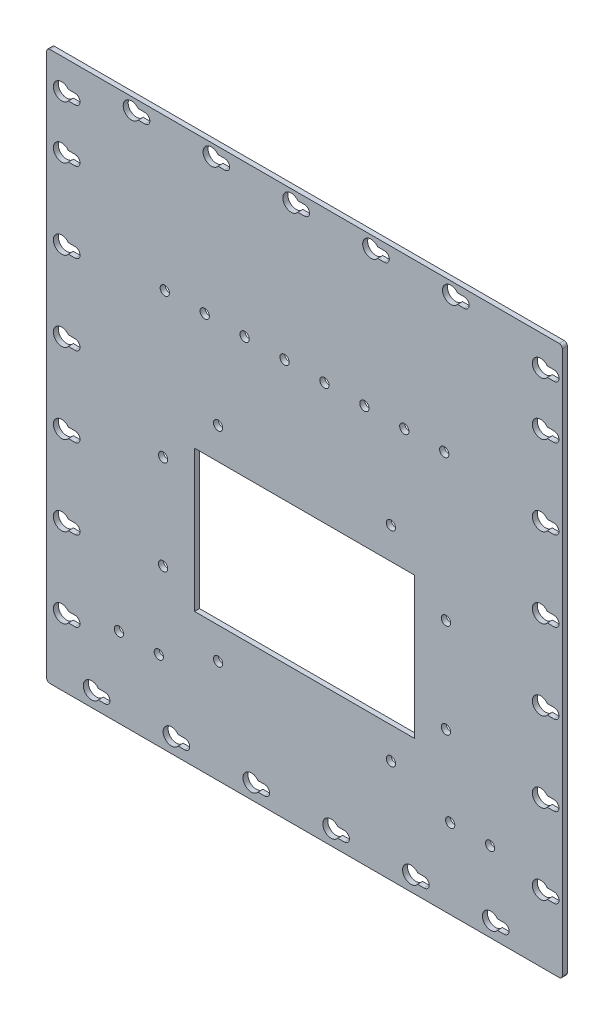
SolidWorks part; units mm, degrees
material "6061 Alloy"
ref_plane "Front Plane" through (0, 0, 0) normal (0, 0, 1) x (1, 0, 0)
ref_plane "Top Plane" through (0, 0, 0) normal (0, 1, 0) x (1, 0, 0)
ref_plane "Right Plane" through (0, 0, 0) normal (1, 0, 0) x (0, 0, -1)
sketch "Sketch1" plane through (0, 0, 0) normal (0, 0, 1) x (1, 0, 0)
  line L0 (0, 0) -> (0, -174.745)
  line L3 (0, -174.745) -> (165.1, -174.745)
  line L5 (0, 0) -> (165.1, 0)
  line L6 (165.1, -174.745) -> (165.1, 0)
  line L7 (82.55, 0) -> (82.55, -174.745) construction
  line L8 (31.75, -2.2625) -> (29.6344, -2.2625)
  line L9 (31.75, -5.4375) -> (29.6344, -5.4375)
  line L10 (9.525, -24.9325) -> (7.4094, -24.9325)
  line L11 (9.525, -28.1075) -> (7.4094, -28.1075)
  line L12 (161.925, -24.9325) -> (159.8094, -24.9325)
  line L13 (161.925, -28.1075) -> (159.8094, -28.1075)
  line L14 (57.15, -2.2625) -> (55.0344, -2.2625)
  line L15 (57.15, -5.4375) -> (55.0344, -5.4375)
  line L16 (82.55, -2.2625) -> (80.4344, -2.2625)
  line L17 (82.55, -5.4375) -> (80.4344, -5.4375)
  line L18 (107.95, -2.2625) -> (105.8344, -2.2625)
  line L19 (107.95, -5.4375) -> (105.8344, -5.4375)
  line L20 (133.35, -2.2625) -> (131.2344, -2.2625)
  line L21 (133.35, -5.4375) -> (131.2344, -5.4375)
  line L22 (9.525, -50.3325) -> (7.4094, -50.3325)
  line L23 (9.525, -53.5075) -> (7.4094, -53.5075)
  line L24 (161.925, -50.3325) -> (159.8094, -50.3325)
  line L25 (161.925, -53.5075) -> (159.8094, -53.5075)
  line L26 (9.525, -75.7325) -> (7.4094, -75.7325)
  line L27 (9.525, -78.9075) -> (7.4094, -78.9075)
  line L28 (161.925, -75.7325) -> (159.8094, -75.7325)
  line L29 (161.925, -78.9075) -> (159.8094, -78.9075)
  line L30 (9.525, -101.1325) -> (7.4094, -101.1325)
  line L31 (9.525, -104.3075) -> (7.4094, -104.3075)
  line L32 (161.925, -101.1325) -> (159.8094, -101.1325)
  line L33 (161.925, -104.3075) -> (159.8094, -104.3075)
  line L34 (9.525, -126.5325) -> (7.4094, -126.5325)
  line L35 (9.525, -129.7075) -> (7.4094, -129.7075)
  line L36 (161.925, -126.5325) -> (159.8094, -126.5325)
  line L37 (161.925, -129.7075) -> (159.8094, -129.7075)
  line L38 (9.525, -151.9325) -> (7.4094, -151.9325)
  line L39 (9.525, -155.1075) -> (7.4094, -155.1075)
  line L40 (161.925, -151.9325) -> (159.8094, -151.9325)
  line L41 (161.925, -155.1075) -> (159.8094, -155.1075)
  line L42 (19.05, -168.395) -> (16.9344, -168.395)
  line L43 (19.05, -171.57) -> (16.9344, -171.57)
  line L44 (44.45, -168.395) -> (42.3344, -168.395)
  line L45 (44.45, -171.57) -> (42.3344, -171.57)
  line L46 (69.85, -168.395) -> (67.7344, -168.395)
  line L47 (69.85, -171.57) -> (67.7344, -171.57)
  line L48 (95.25, -168.395) -> (93.1344, -168.395)
  line L49 (95.25, -171.57) -> (93.1344, -171.57)
  line L50 (120.65, -168.395) -> (118.5344, -168.395)
  line L51 (120.65, -171.57) -> (118.5344, -171.57)
  line L52 (146.05, -168.395) -> (143.9344, -168.395)
  line L53 (146.05, -171.57) -> (143.9344, -171.57)
  line L54 (0.5, 0) -> (0.5, -174.745)
  line L55 (164.6, -174.745) -> (164.6, 0)
  line L56 (0.5, -174.745) -> (164.6, -174.745)
  line L57 (9.525, -8.1) -> (7.4094, -8.1)
  line L58 (9.525, -11.275) -> (7.4094, -11.275)
  line L59 (161.925, -8.1) -> (159.8094, -8.1)
  line L60 (161.925, -11.275) -> (159.8094, -11.275)
  circle A41 centre (9.525, -153.52) radius 1.5875
  circle A42 centre (19.05, -169.9825) radius 1.5875
  circle A43 centre (9.525, -128.12) radius 1.5875
  circle A44 centre (9.525, -102.72) radius 1.5875
  circle A45 centre (9.525, -77.32) radius 1.5875
  circle A46 centre (9.525, -51.92) radius 1.5875
  circle A47 centre (9.525, -26.52) radius 1.5875
  circle A49 centre (44.45, -169.9825) radius 1.5875
  circle A50 centre (69.85, -169.9825) radius 1.5875
  circle A51 centre (95.25, -169.9825) radius 1.5875
  circle A52 centre (120.65, -169.9825) radius 1.5875
  circle A68 centre (146.05, -169.9825) radius 1.5875
  circle A69 centre (107.95, -3.85) radius 1.5875
  circle A70 centre (82.55, -3.85) radius 1.5875
  circle A71 centre (57.15, -3.85) radius 1.5875
  circle A72 centre (9.525, -1.12) radius 1.5875 [skipped]
  circle A73 centre (133.35, -3.85) radius 1.5875
  circle A74 centre (31.75, -3.85) radius 1.5875
  circle A75 centre (161.925, -26.52) radius 1.5875
  circle A76 centre (161.925, -51.92) radius 1.5875
  circle A77 centre (161.925, -77.32) radius 1.5875
  circle A78 centre (161.925, -102.72) radius 1.5875
  circle A79 centre (161.925, -128.12) radius 1.5875
  circle A80 centre (161.925, -153.52) radius 1.5875
  circle A81 centre (27.5125, -3.85) radius 2.65
  circle A83 centre (5.2875, -26.52) radius 2.65
  circle A84 centre (157.6875, -26.52) radius 2.65
  circle A85 centre (52.9125, -3.85) radius 2.65
  circle A86 centre (78.3125, -3.85) radius 2.65
  circle A87 centre (103.7125, -3.85) radius 2.65
  circle A88 centre (129.1125, -3.85) radius 2.65
  circle A89 centre (5.2875, -51.92) radius 2.65
  circle A90 centre (157.6875, -51.92) radius 2.65
  circle A91 centre (5.2875, -77.32) radius 2.65
  circle A92 centre (157.6875, -77.32) radius 2.65
  circle A93 centre (5.2875, -102.72) radius 2.65
  circle A94 centre (157.6875, -102.72) radius 2.65
  circle A95 centre (5.2875, -128.12) radius 2.65
  circle A96 centre (157.6875, -128.12) radius 2.65
  circle A97 centre (5.2875, -153.52) radius 2.65
  circle A98 centre (157.6875, -153.52) radius 2.65
  circle A99 centre (14.8125, -169.9825) radius 2.65
  circle A100 centre (40.2125, -169.9825) radius 2.65
  circle A101 centre (65.6125, -169.9825) radius 2.65
  circle A102 centre (91.0125, -169.9825) radius 2.65
  circle A103 centre (116.4125, -169.9825) radius 2.65
  circle A104 centre (141.8125, -169.9825) radius 2.65
  circle A107 centre (9.525, -9.6875) radius 1.5875
  circle A108 centre (5.2875, -9.6875) radius 2.65
  circle A109 centre (161.925, -9.6875) radius 1.5875
  circle A110 centre (157.6875, -9.6875) radius 2.65
  dimension "D3" = 3.175
  dimension "D8" = 3.175
  dimension "D21" = 5.3
  dimension "D33" = 5.3
  dimension "D1" = 165.1
  dimension "D2" = 174.745
  dimension "D5" = 9.525
  dimension "D4" = 21.225
  dimension "D6" = 19.05
  dimension "D7" = 4.7625
  dimension "D9" = 25.4
  dimension "D10" = 25.4
  dimension "D15" = 25.4
  dimension "D12" = 3.85
  dimension "D13" = 31.75
  dimension "D17" = 31.75
  dimension "D18" = 3.175
  dimension "D20" = 25.4
  dimension "D23" = 25.4
  dimension "D25" = 25.4
  dimension "D27" = 25.4
  dimension "D28" = 0.5
  dimension "D29" = 0.5
  dimension "D34" = 16.8325
  dimension "D35" = 5.8375
  dimension "D11" = 7
  dimension "D14" = 5
  dimension "D16" = 5
  dimension "D19" = 6
  dimension "D22" = 5
  dimension "D24" = 6
  dimension "D26" = 6
extrude "Boss-Extrude1" add sketch "Sketch1" along normal blind 1.5875
fillet "Fillet1" radius 1 4 edges at (164.6, 0, 0.7937) (164.6, -174.745, 0.7937) (0.5, -174.745, 0.7937) (0.5, 0, 0.7937)
sketch "Sketch2" plane through (0, 0, 1.5875) normal (0, 0, 1) x (1, 0, 0)
  line L0 (127.55, -94.3725) -> (37.55, -94.3725) construction
  line L1 (47.55, -86.8725) -> (117.55, -86.8725)
  line L3 (47.55, -131.8725) -> (117.55, -131.8725)
  line L5 (55.05, -76.8725) -> (110.05, -76.8725) construction
  line L6 (55.05, -76.8725) -> (55.05, -141.8725) construction
  line L7 (55.05, -141.8725) -> (110.05, -141.8725) construction
  line L8 (110.05, -76.8725) -> (110.05, -141.8725) construction
  line L9 (37.55, -94.3725) -> (37.55, -124.3725) construction
  line L10 (37.55, -124.3725) -> (127.55, -124.3725) construction
  line L11 (127.55, -124.3725) -> (127.55, -94.3725) construction
  line L12 (82.55, -86.8725) -> (82.55, -131.8725) construction
  line L13 (82.55, 0) -> (82.55, -174.745) construction
  line L14 (1.5, 0) -> (163.6, 0) construction
  line L15 (1.5, -174.745) -> (163.6, -174.745) construction
  line L16 (47.55, -126.8725) -> (117.55, -126.8725) construction
  line L17 (0.5, -87.3725) -> (164.6, -87.3725) construction
  line L18 (0.5, -1) -> (0.5, -173.745) construction
  line L19 (164.6, -173.745) -> (164.6, -1) construction
  line L20 (117.55, -86.8725) -> (117.55, -126.8725)
  line L21 (117.55, -126.8725) -> (117.55, -131.8725)
  line L22 (47.55, -86.8725) -> (47.55, -126.8725)
  line L23 (47.55, -126.8725) -> (47.55, -131.8725)
  circle A0 centre (110.05, -76.8725) radius 1.4732
  circle A1 centre (55.05, -76.8725) radius 1.4732
  circle A2 centre (127.55, -94.3725) radius 1.4732
  circle A3 centre (127.55, -124.3725) radius 1.4732
  circle A4 centre (55.05, -141.8725) radius 1.4732
  circle A5 centre (110.05, -141.8725) radius 1.4732
  circle A6 centre (37.55, -124.3725) radius 1.4732
  circle A7 centre (37.55, -94.3725) radius 1.4732
  point P37 (82.55, -109.3725)
  dimension "D11" = 2.9464
  dimension "D1" = 55
  dimension "D2" = 70
  dimension "D9" = 0
  dimension "D7" = 40
  dimension "D3" = 5
  dimension "D4" = 10
  dimension "D5" = 10
  dimension "D6" = 7.5
  dimension "D8" = 30
  dimension "D12" = 15
  dimension "D13" = 10
  dimension "D14" = 10
  dimension "D10" = 22
extrude "Cut-Extrude1" cut sketch "Sketch2" against normal blind 10
sketch "Sketch3" plane through (0, 0, 1.5875) normal (0, 0, 1) x (1, 0, 0)
  line L0 (82.55, -86.8725) -> (82.55, -131.8725) construction
  line L1 (47.55, -86.8725) -> (117.55, -86.8725) construction
  line L2 (47.55, -131.8725) -> (117.55, -131.8725) construction
sketch "Heat Strap Connections" plane through (0, 0, 1.5875) normal (0, 0, 1) x (1, 0, 0)
  line L0 (1.5, 0) -> (163.6, 0) construction
  line L1 (33.1, -45) -> (43.1, -45) construction
  line L2 (33.1, -45) -> (33.1, -57.7) construction
  line L3 (33.1, -57.7) -> (43.1, -57.7) construction
  line L4 (43.1, -45) -> (43.1, -57.7) construction
  line L5 (18.5, -152.5725) -> (28.5, -152.5725) construction
  line L6 (45.8, -57.7) -> (55.8, -57.7) construction
  line L7 (55.8, -45) -> (55.8, -57.7) construction
  line L8 (45.8, -45) -> (55.8, -45) construction
  line L9 (45.8, -45) -> (45.8, -57.7) construction
  line L10 (58.5, -57.7) -> (68.5, -57.7) construction
  line L11 (68.5, -45) -> (68.5, -57.7) construction
  line L12 (58.5, -45) -> (68.5, -45) construction
  line L13 (58.5, -45) -> (58.5, -57.7) construction
  line L14 (71.2, -57.7) -> (81.2, -57.7) construction
  line L15 (81.2, -45) -> (81.2, -57.7) construction
  line L16 (71.2, -45) -> (81.2, -45) construction
  line L17 (71.2, -45) -> (71.2, -57.7) construction
  line L18 (83.9, -57.7) -> (93.9, -57.7) construction
  line L19 (93.9, -45) -> (93.9, -57.7) construction
  line L20 (83.9, -45) -> (93.9, -45) construction
  line L21 (83.9, -45) -> (83.9, -57.7) construction
  line L22 (96.6, -57.7) -> (106.6, -57.7) construction
  line L23 (106.6, -45) -> (106.6, -57.7) construction
  line L24 (96.6, -45) -> (106.6, -45) construction
  line L25 (96.6, -45) -> (96.6, -57.7) construction
  line L26 (109.3, -57.7) -> (119.3, -57.7) construction
  line L27 (119.3, -45) -> (119.3, -57.7) construction
  line L28 (109.3, -45) -> (119.3, -45) construction
  line L29 (109.3, -45) -> (109.3, -57.7) construction
  line L30 (122, -57.7) -> (132, -57.7) construction
  line L31 (132, -45) -> (132, -57.7) construction
  line L32 (122, -45) -> (132, -45) construction
  line L33 (122, -45) -> (122, -57.7) construction
  line L34 (0.5, -1) -> (0.5, -173.745) construction
  line L35 (28.5, -139.8725) -> (28.5, -152.5725) construction
  line L36 (18.5, -139.8725) -> (28.5, -139.8725) construction
  line L37 (18.5, -139.8725) -> (18.5, -152.5725) construction
  line L38 (136.6, -152.5725) -> (146.6, -152.5725) construction
  line L39 (47.55, -109.3725) -> (117.55, -109.3725) construction
  line L40 (47.55, -86.8725) -> (47.55, -131.8725) construction
  line L41 (117.55, -86.8725) -> (117.55, -131.8725) construction
  line L42 (146.6, -139.8725) -> (146.6, -152.5725) construction
  line L43 (136.6, -139.8725) -> (146.6, -139.8725) construction
  line L44 (136.6, -139.8725) -> (136.6, -152.5725) construction
  line L45 (31.2, -152.5725) -> (41.2, -152.5725) construction
  line L46 (41.2, -139.8725) -> (41.2, -152.5725) construction
  line L47 (31.2, -139.8725) -> (41.2, -139.8725) construction
  line L48 (31.2, -139.8725) -> (31.2, -152.5725) construction
  line L49 (123.9, -152.5725) -> (133.9, -152.5725) construction
  line L50 (133.9, -139.8725) -> (133.9, -152.5725) construction
  line L51 (123.9, -139.8725) -> (133.9, -139.8725) construction
  line L52 (123.9, -139.8725) -> (123.9, -152.5725) construction
  circle A0 centre (38.1, -48.175) radius 1.4732
  circle A1 centre (50.8, -48.175) radius 1.4732
  circle A2 centre (63.5, -48.175) radius 1.4732
  circle A3 centre (76.2, -48.175) radius 1.4732
  circle A4 centre (88.9, -48.175) radius 1.4732
  circle A5 centre (101.6, -48.175) radius 1.4732
  circle A6 centre (114.3, -48.175) radius 1.4732
  circle A7 centre (127, -48.175) radius 1.4732
  circle A8 centre (23.5, -149.3975) radius 1.4732
  circle A9 centre (141.6, -149.3975) radius 1.4732
  circle A10 centre (36.2, -149.3975) radius 1.4732
  circle A11 centre (128.9, -149.3975) radius 1.4732
  point P4 (38.1, -57.7)
  point P82 (0, 0)
  point P83 (49.9113, -147.1011)
  point P84 (23.5, -139.8725)
  point P85 (36.2, -139.8725)
  point P86 (128.9, -139.8725)
  point P87 (141.6, -139.8725)
  point P88 (29.1131, -147.486)
  point P89 (36.3338, -144.4119)
  point P90 (63.5, -145.0483)
  point P91 (56.5237, -156.6841)
  point P92 (35.4452, -143.8303)
  point P93 (33.1, -150.2913)
  point P94 (27.6649, -149.3481)
  point P95 (130.8347, -149.513)
  point P96 (18.7112, -147.4825)
  point P97 (37.9258, -145.6987)
  point P98 (22.8132, -146.4542)
  point P99 (23.5, -149.0937)
  dimension "D4" = 2.9464
  dimension "D2" = 10
  dimension "D3" = 12.7
  dimension "D1" = 3.175
  dimension "D5" = 45
  dimension "D8" = 12.7
  dimension "D6" = 37.6
  dimension "D10" = 12.7
  dimension "D11" = 12.7
  dimension "D12" = 8
  dimension "D13" = 6.35
  dimension "D14" = 6.35
  dimension "D9" = 3.175
  dimension "D7" = 8
extrude "Cut-Extrude2" cut sketch "Heat Strap Connections" against normal through all
equation "\"D8@Sketch1\"=\"D3@Sketch1\""
equation "\"D29@Sketch1\"=\"D28@Sketch1\""
equation "\"D5@Sketch2\"=\"D4@Sketch2\""
equation "\"D6@Sketch2\"=(\"D2@Sketch2\"-\"D1@Sketch2\")/2"
equation "\"D12@Sketch2\"=((\"D7@Sketch2\"+\"D3@Sketch2\") - \"D8@Sketch2\")"
equation "\"D13@Sketch2\"=\"D4@Sketch2\""
equation "\"D14@Sketch2\"=\"D13@Sketch2\""
equation "\"D11@Heat Strap Connections\"=\"D10@Heat Strap Connections\""
equation "\"D14@Heat Strap Connections\"=\"D13@Heat Strap Connections\""
